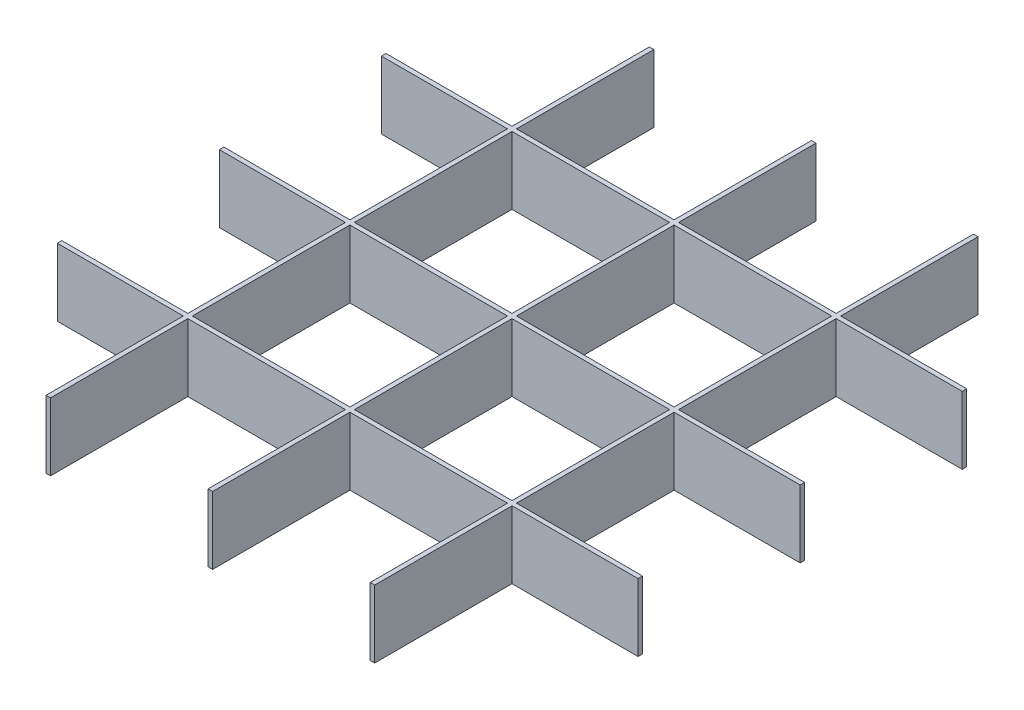
SolidWorks part; units mm, degrees
ref_plane "前视基准面" through (0, 0, 0) normal (0, 0, 1) x (1, 0, 0)
ref_plane "上视基准面" through (0, 0, 0) normal (0, 1, 0) x (1, 0, 0)
ref_plane "右视基准面" through (0, 0, 0) normal (1, 0, 0) x (0, 0, -1)
other "Configuration Table"
sketch "草图1" plane through (0, 0, 0) normal (0, 1, 0) x (1, 0, 0)
  line L0 (-129, 0) -> (129, 0) construction
  line L1 (129, -134) -> (-129, -134) construction
  line L2 (129, -134) -> (129, 134) construction
  line L3 (129, 134) -> (-129, 134) construction
  line L4 (-129, -134) -> (-129, 134) construction
  line L5 (129, -134) -> (-129, 134) construction
  line L6 (129, 134) -> (-129, -134) construction
  line L7 (0, 134) -> (0, -134) construction
  line L8 (-71, 73) -> (-1, 73)
  line L9 (-129, 73) -> (-73, 73)
  line L10 (-129, 73) -> (-129, 71)
  line L11 (-129, 71) -> (-73, 71)
  line L12 (129, 73) -> (129, 71)
  line L13 (-129, 1) -> (-73, 1)
  line L14 (-129, 1) -> (-129, -1)
  line L15 (-129, -1) -> (-73, -1)
  line L16 (129, 1) -> (129, -1)
  line L17 (-129, -71) -> (-73, -71)
  line L18 (-129, -71) -> (-129, -73)
  line L19 (-129, -73) -> (-73, -73)
  line L20 (129, -71) -> (129, -73)
  line L21 (-73, 134) -> (-71, 134)
  line L22 (-73, 134) -> (-73, 73)
  line L23 (-73, -134) -> (-71, -134)
  line L24 (-71, 134) -> (-71, 73)
  line L25 (-1, 134) -> (1, 134)
  line L26 (-1, 134) -> (-1, 73)
  line L27 (-1, -134) -> (1, -134)
  line L28 (1, 134) -> (1, 73)
  line L29 (71, 134) -> (73, 134)
  line L30 (71, 134) -> (71, 73)
  line L31 (71, -134) -> (73, -134)
  line L32 (73, 134) -> (73, 73)
  line L33 (-71, 71) -> (-1, 71)
  line L34 (-71, 71) -> (-71, 1)
  line L35 (-73, 71) -> (-73, 1)
  line L36 (-71, 1) -> (-1, 1)
  line L37 (-71, -1) -> (-71, -71)
  line L38 (-73, -1) -> (-73, -71)
  line L39 (-71, -1) -> (-1, -1)
  line L40 (-71, -71) -> (-1, -71)
  line L41 (-71, -73) -> (-1, -73)
  line L42 (-73, -73) -> (-73, -134)
  line L43 (-71, -73) -> (-71, -134)
  line L44 (-1, -73) -> (-1, -134)
  line L45 (1, -71) -> (71, -71)
  line L46 (1, -73) -> (71, -73)
  line L47 (1, -73) -> (1, -134)
  line L48 (71, -73) -> (71, -134)
  line L49 (73, -73) -> (73, -134)
  line L50 (73, -73) -> (129, -73)
  line L51 (73, -71) -> (129, -71)
  line L52 (1, 71) -> (71, 71)
  line L53 (1, 73) -> (71, 73)
  line L54 (-1, 71) -> (-1, 1)
  line L55 (1, 71) -> (1, 1)
  line L56 (73, 73) -> (129, 73)
  line L57 (71, 71) -> (71, 1)
  line L58 (73, 71) -> (73, 1)
  line L59 (73, 71) -> (129, 71)
  line L60 (73, 1) -> (129, 1)
  line L61 (1, 1) -> (71, 1)
  line L62 (-1, -1) -> (-1, -71)
  line L63 (1, -1) -> (1, -71)
  line L64 (71, -1) -> (71, -71)
  line L65 (1, -1) -> (71, -1)
  line L66 (73, -1) -> (129, -1)
  line L67 (73, -1) -> (73, -71)
  point P0 (0, 0)
  dimension "D1" = 258
  dimension "D2" = 268
  dimension "D3" = 2
  dimension "D4" = 70
extrude "凸台-拉伸2" add sketch "草图1" along normal blind 30
